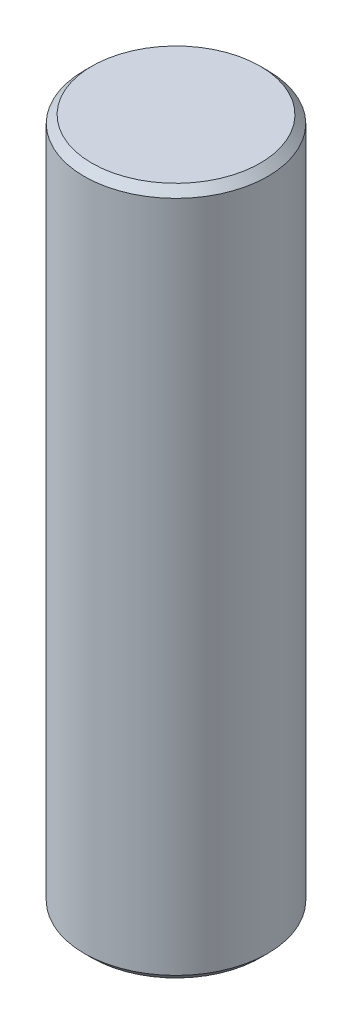
SolidWorks part; units mm, degrees
ref_plane "Front Plane" through (0, 0, 0) normal (0, 0, 1) x (1, 0, 0)
ref_plane "Top Plane" through (0, 0, 0) normal (0, 1, 0) x (1, 0, 0)
ref_plane "Right Plane" through (0, 0, 0) normal (1, 0, 0) x (0, 0, -1)
sketch "Sketch1" plane through (0, 0, 0) normal (0, 0, 1) x (1, 0, 0)
  line L0 (0, 0) -> (0, 45)
  line L1 (0, 45) -> (-6, 45)
  line L2 (-6, 45) -> (-6, 0)
  line L3 (-6, 0) -> (0, 0)
  dimension "D1" = 45
  dimension "D2" = 6
revolve "Revolve1" add sketch "Sketch1" angle 360 about L0
chamfer "Chamfer1" distance 0.5 angle 45 2 edges at (0, 0, -6) (0, 45, -6)
